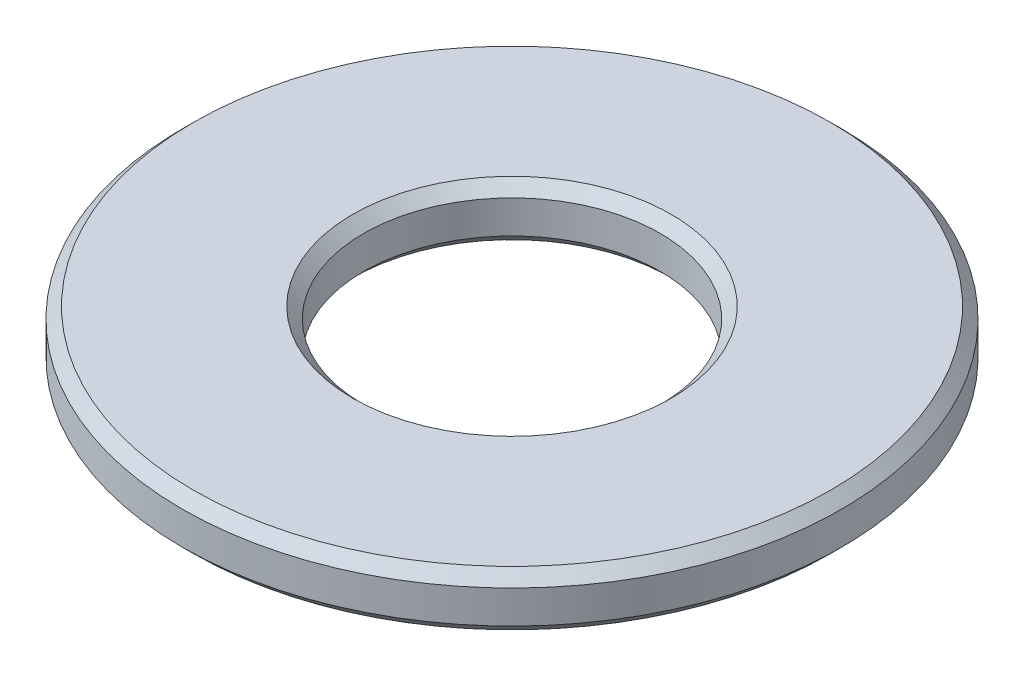
SolidWorks part; units mm, degrees
ref_plane "Front Plane" through (0, 0, 0) normal (0, 0, 1) x (1, 0, 0)
ref_plane "Top Plane" through (0, 0, 0) normal (0, 1, 0) x (1, 0, 0)
ref_plane "Right Plane" through (0, 0, 0) normal (1, 0, 0) x (0, 0, -1)
sketch "Sketch1" plane through (0, 0, 0) normal (0, 1, 0) x (1, 0, 0)
  circle A0 centre (0, 0) radius 1.35
  circle A1 centre (0, 0) radius 3
  dimension "D1" = 2.7
  dimension "D2" = 6
extrude "Boss-Extrude1" add sketch "Sketch1" along normal blind 0.5
chamfer "Chamfer1" distance 0.1 angle 45 4 edges at (0, 0, 1.35) (0, 0, 3) (0, 0.5, 3) (0, 0.5, 1.35)
